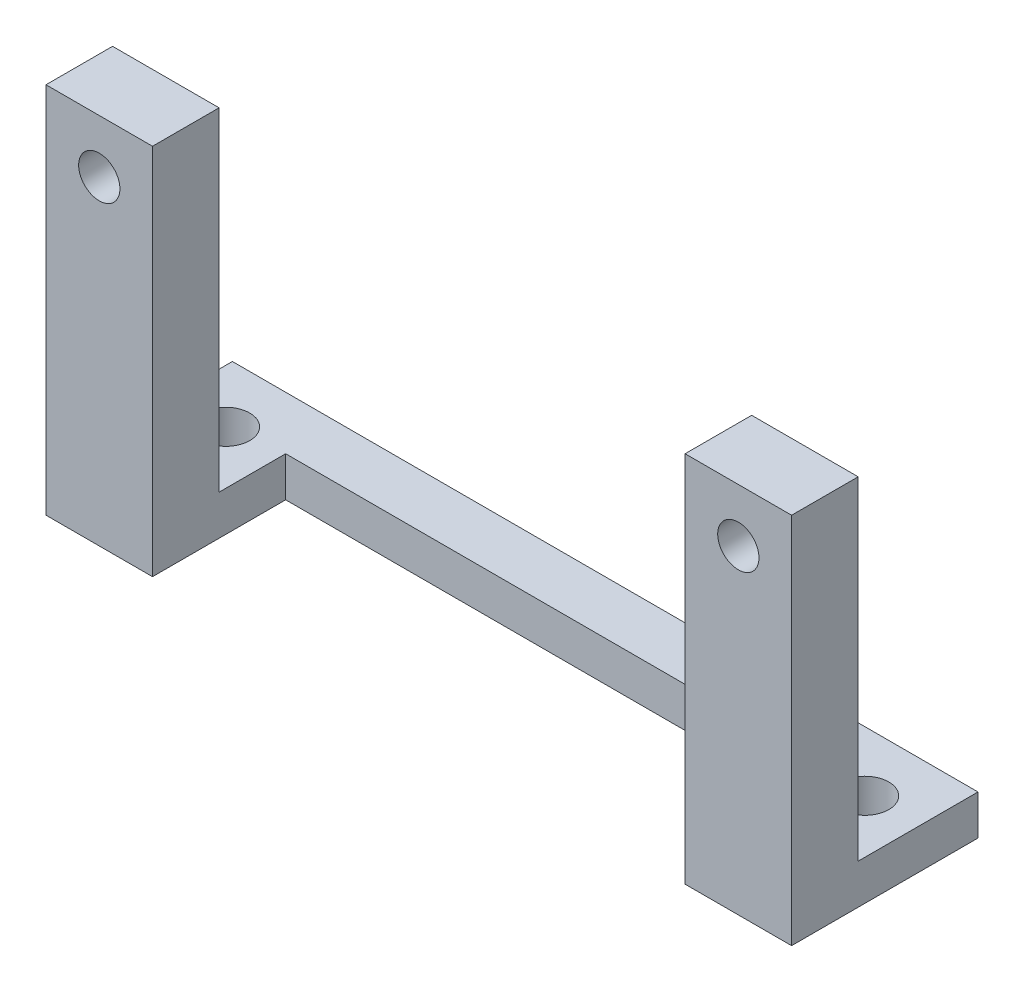
SolidWorks part; units mm, degrees
ref_plane "前视基准面" through (0, 0, 0) normal (0, 0, 1) x (1, 0, 0)
ref_plane "上视基准面" through (0, 0, 0) normal (0, 1, 0) x (1, 0, 0)
ref_plane "右视基准面" through (0, 0, 0) normal (1, 0, 0) x (0, 0, -1)
sketch "草图1" plane through (0, 0, 0) normal (0, 1, 0) x (1, 0, 0)
  line L0 (-28, 9) -> (28, 9)
  line L1 (28, 9) -> (28, -5)
  line L2 (28, -5) -> (-28, -5)
  line L3 (-28, -5) -> (-28, 9)
  dimension "D1" = 28
  dimension "D2" = 9
  dimension "D3" = 28
  dimension "D4" = 9
  dimension "D5" = 28
  dimension "D6" = 5
  dimension "D7" = 28
  dimension "D8" = 5
extrude "相机小底脚56x14_厚3_单向3mm" add sketch "草图1" along normal blind 3
sketch "草图2" plane through (0, 0, 0) normal (0, 1, 0) x (1, 0, 0)
  line L0 (-20, -6) -> (20, -6)
  line L1 (20, -6) -> (20, 5)
  line L2 (20, 5) -> (-20, 5)
  line L3 (-20, 5) -> (-20, -6)
  dimension "D1" = 20
  dimension "D2" = 6
  dimension "D3" = 20
  dimension "D4" = 6
  dimension "D5" = 20
  dimension "D6" = 5
  dimension "D7" = 20
  dimension "D8" = 5
extrude "底脚中央40宽镂空_只留后横梁4_贯穿底脚3" cut sketch "草图2" along normal blind 3
sketch "草图3" plane through (0, 0, 0) normal (0, 0, 1) x (1, 0, 0)
  line L0 (-28, 3) -> (-20, 3)
  line L1 (-20, 3) -> (-20, 28)
  line L2 (-20, 28) -> (-28, 28)
  line L3 (-28, 28) -> (-28, 3)
  line L4 (20, 3) -> (28, 3)
  line L5 (28, 3) -> (28, 28)
  line L6 (28, 28) -> (20, 28)
  line L7 (20, 28) -> (20, 3)
  dimension "D1" = 28
  dimension "D2" = 3
  dimension "D3" = 20
  dimension "D4" = 3
  dimension "D5" = 20
  dimension "D6" = 28
  dimension "D7" = 28
  dimension "D8" = 28
  dimension "D9" = 20
  dimension "D10" = 3
  dimension "D11" = 28
  dimension "D12" = 3
  dimension "D13" = 28
  dimension "D14" = 28
  dimension "D15" = 20
  dimension "D16" = 28
extrude "双耳支撑臂厚5_沿用M2.5x10尺寸链" add sketch "草图3" along normal blind 5
sketch "草图4" plane through (0, 0, 0) normal (0, 0, 1) x (1, 0, 0)
  circle A0 centre (-24, 24) radius 1.55
  circle A1 centre (24, 24) radius 1.55
  dimension "D1" = 3.1
  dimension "D2" = 24
  dimension "D3" = 24
  dimension "D4" = 24
extrude "双耳原孔3.1_孔距48_圆孔不加大_贯穿" cut sketch "草图4" along normal blind 5
sketch "草图5" plane through (0, 0, 0) normal (0, 1, 0) x (1, 0, 0)
  circle A0 centre (-24, 4.5) radius 1.8
  circle A1 centre (24, 4.5) radius 1.8
  dimension "D1" = 3.6
  dimension "D2" = 24
  dimension "D3" = 24
  dimension "D4" = 4.5
extrude "底脚圆孔_无长槽" cut sketch "草图5" along normal blind 3
